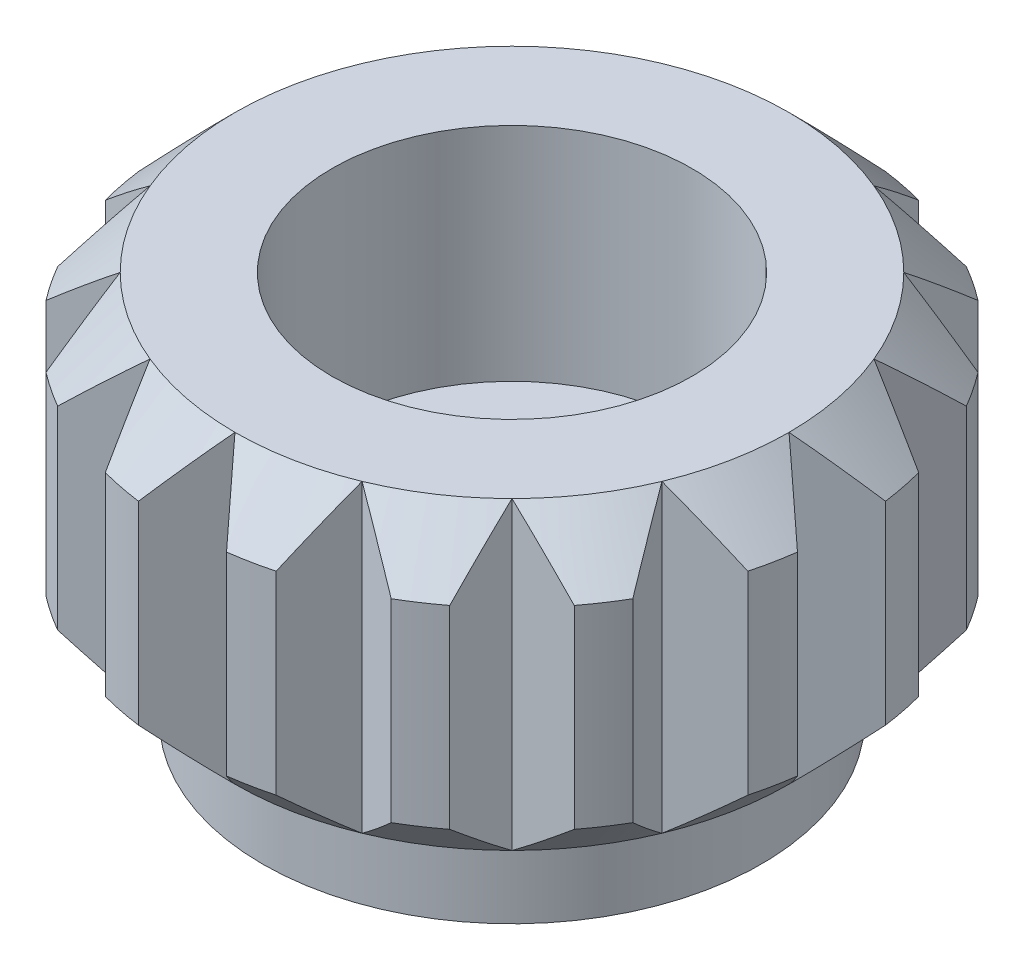
SolidWorks part; units mm, degrees
ref_plane "Plan de face" through (0, 0, 0) normal (0, 0, 1) x (1, 0, 0)
ref_plane "Plan de dessus" through (0, 0, 0) normal (0, 1, 0) x (1, 0, 0)
ref_plane "Plan de droite" through (0, 0, 0) normal (1, 0, 0) x (0, 0, -1)
sketch "Esquisse1" plane through (0, 0, 0) normal (0, 1, 0) x (1, 0, 0)
  circle A0 centre (0, 0) radius 6
  dimension "D1" = 12
extrude "Boss.-Extru.1" add sketch "Esquisse1" along normal blind 7
sketch "Esquisse2" plane through (0, 0, 0) normal (0, -1, 0) x (1, 0, 0)
  circle A2 centre (0, 0) radius 4.5
  circle A3 centre (0, 0) radius 4.5
  dimension "D1" = 1.5
extrude "Enlèv. mat.-Extru.1" cut sketch "Esquisse2" against normal blind 1.5 flip side to cut
chamfer "Chanfrein1" distance 1 angle 45 2 edges at (0, 7, 6) (0, 1.5, -6)
hole_wizard "Chambrage pour vis à tête cylindrique à 6 pans creux (ou vis CHC) M31" positions "Esquisse3" profile "Esquisse4" counterbore size "M3" standard "Ansi Metric" end condition through all
sketch "Esquisse3" plane through (0, 7, 0) normal (0, 1, 0) x (1, 0, 0)
  point P0 (0, 0)
sketch "Esquisse4" plane through (0, 7, 0) normal (1, 0, 0) x (0, 0, 1)
  line L0 (0, 0) -> (0, 7)
  line L1 (0, 7) -> (1.6, 7)
  line L3 (1.6, 7) -> (1.6, 4)
  line L4 (1.6, 4) -> (3.25, 4)
  line L5 (3.25, 4) -> (3.25, 0)
  line L7 (3.25, 0) -> (0, 0)
  line L11 (0, -6.35) -> (0, 107.95) construction
  dimension "Diamètre du perçage jusqu'au prochain" = 3.2
  dimension "Profondeur du perçage jusqu'au prochain" = 7
  dimension "Diamètre du chambrage" = 6.5
  dimension "Profondeur du chambrage" = 4
sketch "Esquisse5" plane through (0, 7, 0) normal (0, 1, 0) x (1, 0, 0)
  line L0 (-5, 0) -> (-6.6456, 1.3809)
  line L1 (-6.6456, 1.3809) -> (-6.6456, -1.3809)
  line L2 (-6.6456, -1.3809) -> (-5, 0)
  line L3 (-6.6456, 0) -> (0, 0) construction
  circle A0 centre (0, 0) radius 5 construction
  dimension "D1" = 80
extrude "Enlèv. mat.-Extru.2" cut sketch "Esquisse5" against normal through all
pattern_circular "Répétition circulaire1" count 16 over 360 about axis through (0, 0, 0) along (0, 1, 0) of "Enlèv. mat.-Extru.2"
